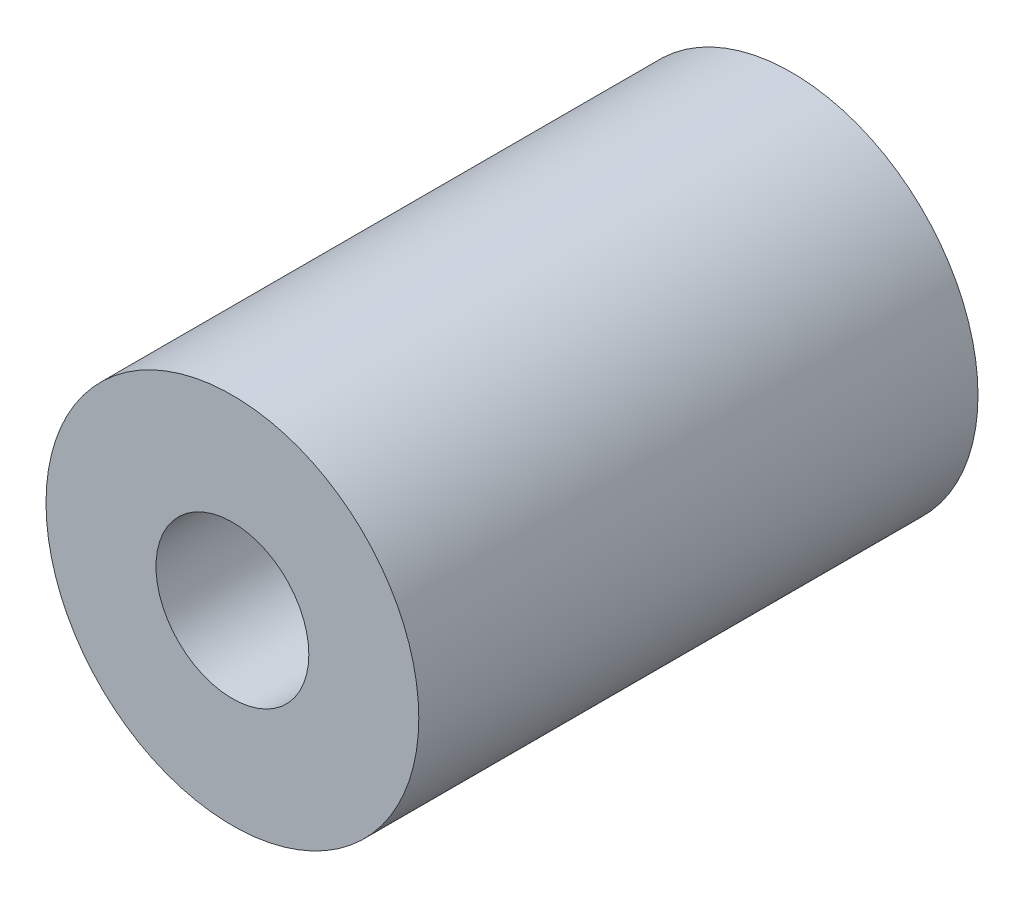
SolidWorks part; units mm, degrees
ref_plane "正面" through (0, 0, 0) normal (0, 0, 1) x (1, 0, 0)
ref_plane "平面" through (0, 0, 0) normal (0, 1, 0) x (1, 0, 0)
ref_plane "右側面" through (0, 0, 0) normal (1, 0, 0) x (0, 0, -1)
sketch "ｽｹｯﾁ2" plane through (0, 0, 0) normal (0, 0, 1) x (1, 0, 0)
  circle A0 centre (0, 0) radius 10
  circle A1 centre (0, 0) radius 4.1
  dimension "D1" = 8.2
  dimension "D2" = 20
extrude "ﾎﾞｽ - 押し出し1" add sketch "ｽｹｯﾁ2" along normal blind 30
